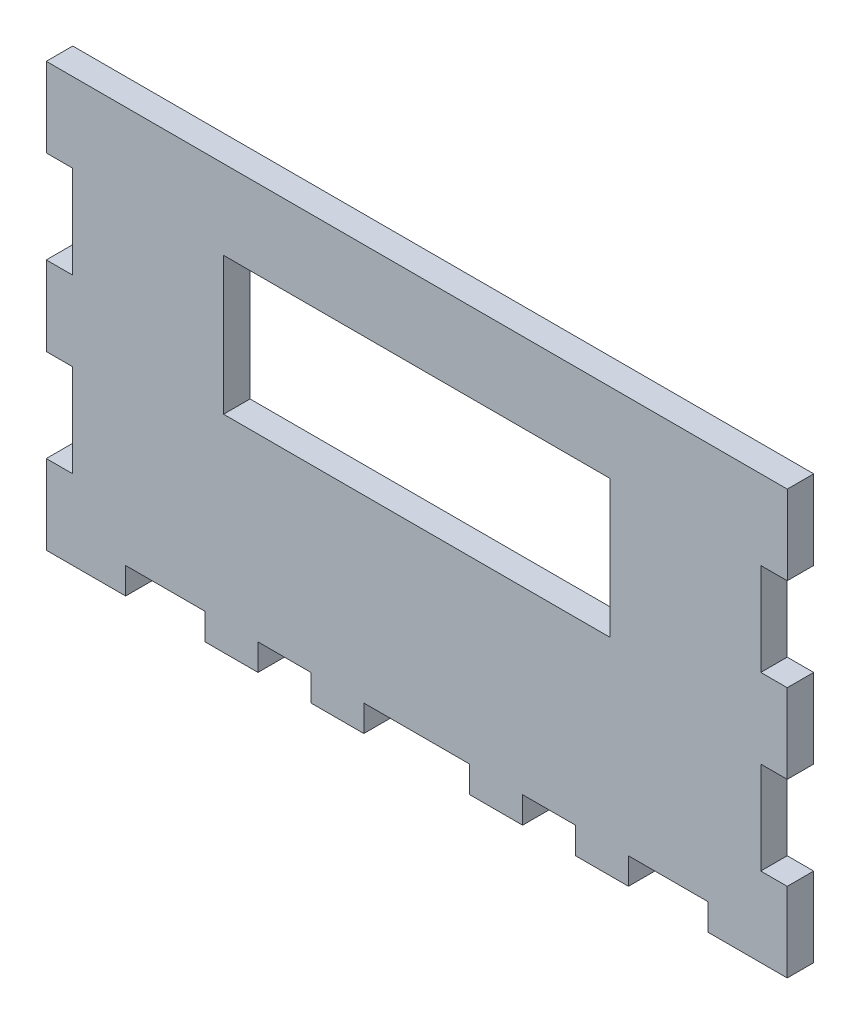
SolidWorks part; units mm, degrees
ref_plane "Front Plane" through (0, 0, 0) normal (0, 0, 1) x (1, 0, 0)
ref_plane "Top Plane" through (0, 0, 0) normal (0, 1, 0) x (1, 0, 0)
ref_plane "Right Plane" through (0, 0, 0) normal (1, 0, 0) x (0, 0, -1)
sketch "Sketch1" plane through (0, 0, 0) normal (0, 0, 1) x (1, 0, 0)
  line L0 (69.0386, -4.6833) -> (64.0386, -4.6833)
  line L1 (-37.4553, 1.8167) -> (35.5447, 1.8167)
  line L2 (-37.4553, 1.8167) -> (-37.4553, 27.8167)
  line L3 (-37.4553, 27.8167) -> (35.5447, 27.8167)
  line L4 (35.5447, 1.8167) -> (35.5447, 27.8167)
  line L5 (-65.9553, 27.8167) -> (-65.9553, 10.3167)
  line L6 (-65.9553, -4.6833) -> (-65.9553, -22.1833)
  line L7 (-70.9553, 42.8167) -> (69.0447, 42.8167)
  line L8 (-40.9553, -37.1833) -> (-30.9553, -37.1833)
  line L9 (-70.9553, -37.1833) -> (-55.9553, -37.1833)
  line L10 (69.0447, 42.8167) -> (69.0447, 27.8167)
  line L11 (64.0386, -4.6833) -> (64.0386, -22.1833)
  line L12 (-55.9553, -37.1833) -> (-55.9553, -32.1833)
  line L13 (-55.9553, -32.1833) -> (-40.9553, -32.1833)
  line L14 (69.0386, -37.1833) -> (69.0386, -22.1833)
  line L15 (69.0386, -22.1833) -> (64.0386, -22.1833)
  line L16 (-70.9553, -37.1833) -> (-55.9553, -37.1833)
  line L17 (69.0386, -4.6833) -> (69.0386, 10.3167)
  line L18 (69.0386, 10.3167) -> (64.0386, 10.3167)
  line L19 (-40.9553, -37.1833) -> (-40.9553, -32.1833)
  line L20 (-65.9553, -4.6833) -> (-70.9553, -4.6833)
  line L23 (-55.9553, -37.1833) -> (-55.9553, -32.1833)
  line L24 (-65.9553, 27.8167) -> (-70.9553, 27.8167)
  line L25 (-70.9553, 42.8167) -> (-70.9553, 27.8167)
  line L27 (69.0386, -37.1833) -> (54.0386, -37.1833)
  line L28 (-65.9553, -22.1833) -> (-70.9553, -22.1833)
  line L29 (-70.9553, -37.1833) -> (-70.9553, -22.1833)
  line L31 (-65.9553, 10.3167) -> (-70.9553, 10.3167)
  line L32 (-70.9553, -4.6833) -> (-70.9553, 10.3167)
  line L34 (-70.9553, 27.8167) -> (-65.9553, 27.8167)
  line L35 (54.0386, -37.1833) -> (54.0386, -32.1833)
  line L36 (-70.9553, 10.3167) -> (-65.9553, 10.3167)
  line L37 (-65.9553, 27.8167) -> (-65.9553, 10.3167)
  line L38 (-70.9553, -4.6833) -> (-65.9553, -4.6833)
  line L39 (54.0386, -37.1833) -> (54.0386, -32.1833)
  line L40 (-70.9553, -22.1833) -> (-65.9553, -22.1833)
  line L41 (-65.9553, -4.6833) -> (-65.9553, -22.1833)
  line L42 (64.0386, -4.6833) -> (69.0386, -4.6833)
  line L43 (64.0386, -4.6833) -> (64.0386, -22.1833)
  line L44 (64.0386, -22.1833) -> (69.0386, -22.1833)
  line L45 (54.0386, -32.1833) -> (39.0386, -32.1833)
  line L46 (64.0386, 27.8167) -> (69.0447, 27.8167)
  line L47 (64.0386, 27.8167) -> (64.0386, 10.3167)
  line L48 (64.0386, 10.3167) -> (69.0386, 10.3167)
  line L49 (39.0386, -37.1833) -> (39.0386, -32.1833)
  line L50 (-30.9553, -37.1833) -> (-30.9553, -32.1833)
  line L52 (-40.9553, -32.1833) -> (-40.9553, -37.1833)
  line L54 (-30.9553, -32.1833) -> (-30.9553, -37.1833)
  line L55 (-30.9553, -32.1833) -> (-20.9553, -32.1833)
  line L56 (-30.9553, -32.1833) -> (-30.9553, -37.1833)
  line L58 (-20.9553, -32.1833) -> (-20.9553, -37.1833)
  line L59 (-20.9553, -37.1833) -> (-20.9553, -32.1833)
  line L61 (-20.9553, -32.1833) -> (-20.9553, -37.1833)
  line L62 (-20.9553, -37.1833) -> (-10.9553, -37.1833)
  line L63 (-10.9553, -32.1833) -> (-10.9553, -37.1833)
  line L64 (-10.9553, -37.1833) -> (-10.9553, -32.1833)
  line L65 (-10.9553, -32.1833) -> (-0.9553, -32.1833)
  line L66 (-10.9553, -32.1833) -> (-10.9553, -37.1833)
  line L70 (-0.9553, -32.1833) -> (9.0447, -32.1833)
  line L73 (9.0447, -32.1833) -> (9.0447, -37.1833)
  line L74 (9.0447, -37.1833) -> (9.0447, -32.1833)
  line L76 (9.0447, -32.1833) -> (9.0447, -37.1833)
  line L77 (9.0447, -37.1833) -> (19.0447, -37.1833)
  line L78 (19.0447, -32.1833) -> (19.0447, -37.1833)
  line L79 (19.0447, -37.1833) -> (19.0447, -32.1833)
  line L80 (19.0447, -32.1833) -> (29.0447, -32.1833)
  line L81 (19.0447, -32.1833) -> (19.0447, -37.1833)
  line L83 (29.0447, -32.1833) -> (29.0447, -37.1833)
  line L84 (29.0447, -37.1833) -> (29.0447, -32.1833)
  line L86 (29.0447, -32.1833) -> (29.0447, -37.1833)
  line L87 (29.0447, -37.1833) -> (39.0447, -37.1833)
  line L88 (39.0447, -32.1833) -> (39.0447, -37.1833)
  line L89 (-55.9553, -37.1833) -> (-40.9553, -37.1833) [skipped]
  line L91 (54.0386, -37.1833) -> (39.0386, -37.1833) [skipped]
  line L92 (-0.9553, -32.1833) -> (-0.9553, -37.1833) [skipped]
  line L93 (-0.9553, -37.1833) -> (-0.9553, -32.1833) [skipped]
  line L94 (-0.9553, -32.1833) -> (-0.9553, -37.1833) [skipped]
  point P0 (0, 0)
  point P6 (0, 14.8167)
  dimension "D1" = 73
  dimension "D2" = 26
  dimension "D3" = 140
  dimension "D4" = 80
  dimension "D5" = 15
  dimension "D6" = 10
  dimension "D10" = 2
  dimension "D8" = 2
  dimension "D12" = 8
extrude "Boss-Extrude1" add sketch "Sketch1" along normal blind 5 contours L83 L87 L49 L45 L35 L27 L14 L15 L11 L0 L17 L18 L47 L46 L10 L7 L25 L24 L5 L31 L32 L20 L6 L28 L29 L9 L12 L13 L19 L8 L50 L55 L58 L62 L63 L65 L70 L73 L77 L78 L80 L4 L1 L2 L3
